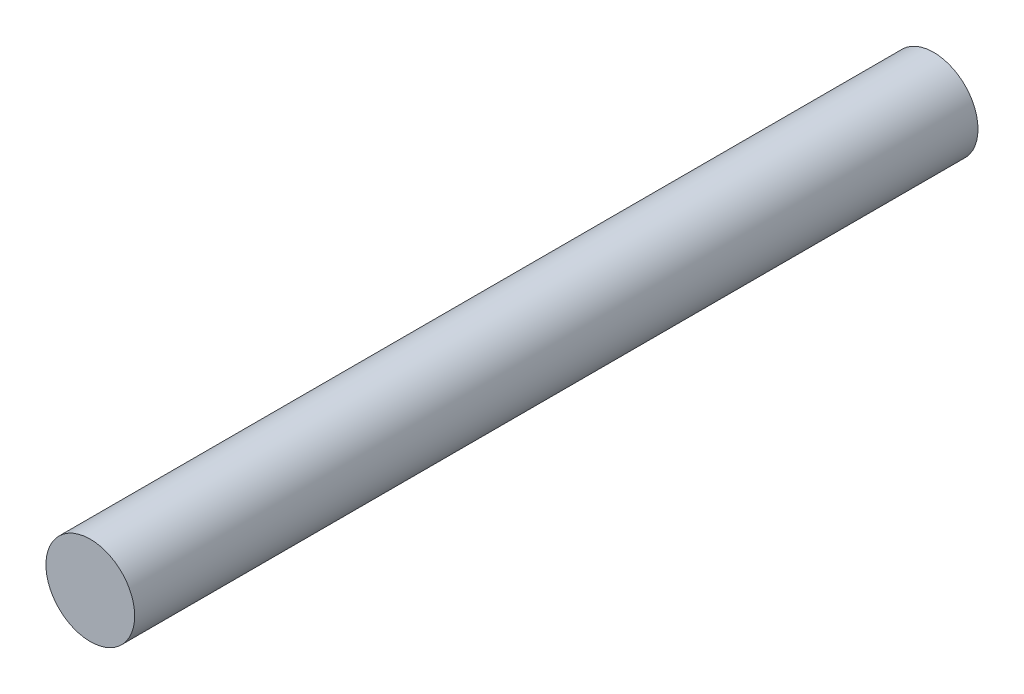
SolidWorks part; units mm, degrees
material "AISI 4340 Steel, normalized"
ref_plane "Front Plane" through (0, 0, 0) normal (0, 0, 1) x (1, 0, 0)
ref_plane "Top Plane" through (0, 0, 0) normal (0, 1, 0) x (1, 0, 0)
ref_plane "Right Plane" through (0, 0, 0) normal (1, 0, 0) x (0, 0, -1)
sketch "Sketch1" plane through (0, 0, 0) normal (0, 0, 1) x (1, 0, 0)
  circle A0 centre (0, 0) radius 2
  dimension "D1" = 4
extrude "Boss-Extrude1" add sketch "Sketch1" along normal blind 38
